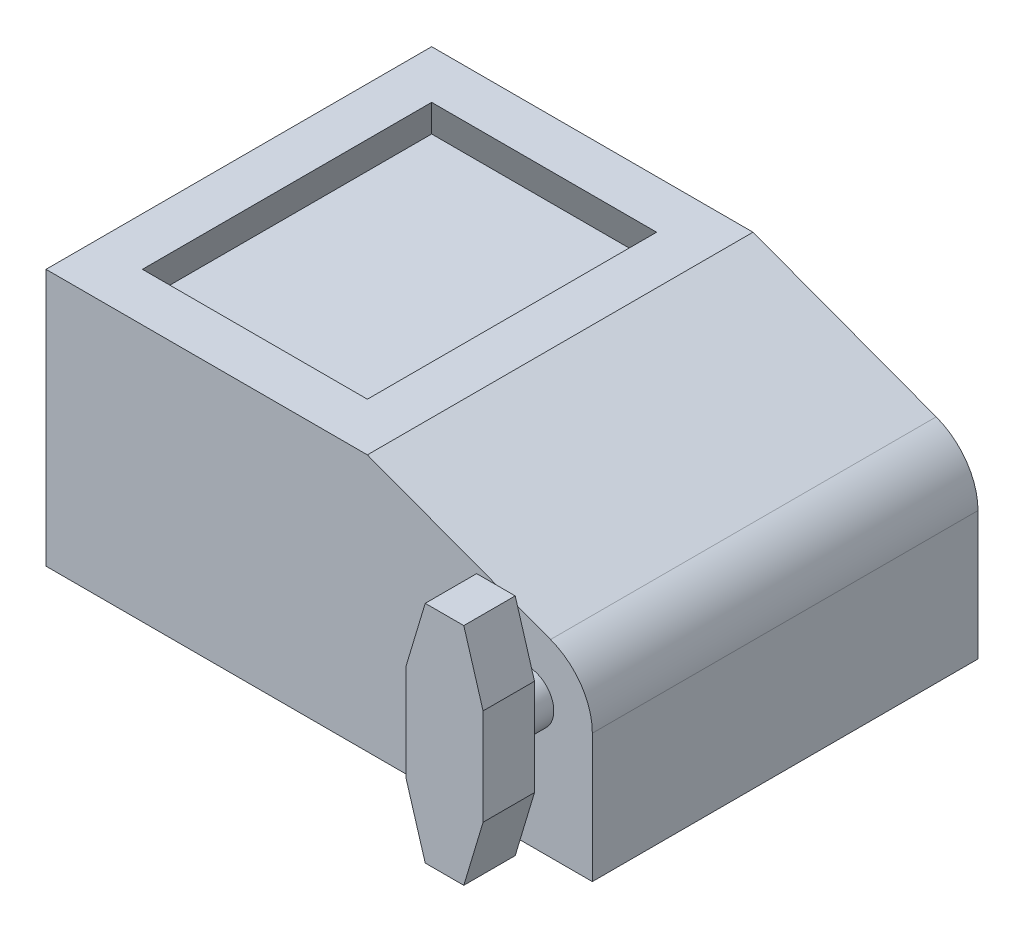
SolidWorks part; units mm, degrees
ref_plane "Front Plane" through (0, 0, 0) normal (0, 0, 1) x (1, 0, 0)
ref_plane "Top Plane" through (0, 0, 0) normal (0, 1, 0) x (1, 0, 0)
ref_plane "Right Plane" through (0, 0, 0) normal (1, 0, 0) x (0, 0, -1)
sketch "Sketch1" plane through (0, 0, 0) normal (0, 1, 0) x (1, 0, 0)
  line L1 (-25, -30) -> (25, -30)
  line L2 (-25, -30) -> (-25, 30)
  line L3 (-25, 30) -> (25, 30)
  line L4 (25, -30) -> (25, 30)
  line L5 (-25, -30) -> (25, 30) construction
  line L6 (-25, 30) -> (25, -30) construction
  point P0 (0, 0)
  dimension "D1" = 50
  dimension "D2" = 60
extrude "Boss-Extrude1" add sketch "Sketch1" along normal blind 40
sketch "Sketch2" plane through (0, 0, 30) normal (0, 0, 1) x (1, 0, 0)
  line L0 (-25, 40) -> (25, 40) construction
  line L1 (25, 40) -> (25, 0) construction
  line L2 (25, 40) -> (53.4954, 29.3692)
  line L3 (25, 0) -> (60, 0)
  line L4 (25, 40) -> (25, 0)
  line L5 (60, 20) -> (60, 0)
  circle A0 centre (50, 20) radius 10
  dimension "D3" = 20
  dimension "D1" = 20
  dimension "D2" = 25
extrude "Boss-Extrude2" add sketch "Sketch2" against normal up to surface (60 mm away)
sketch "Sketch3" plane through (0, 40, 0) normal (0, 1, 0) x (1, 0, 0)
  line L1 (-17.5, -22.5) -> (17.5, -22.5)
  line L2 (-17.5, -22.5) -> (-17.5, 22.5)
  line L3 (-17.5, 22.5) -> (17.5, 22.5)
  line L4 (17.5, -22.5) -> (17.5, 22.5)
  line L5 (-17.5, -22.5) -> (17.5, 22.5) construction
  line L6 (-17.5, 22.5) -> (17.5, -22.5) construction
  point P0 (0, 0)
  dimension "D1" = 35
  dimension "D2" = 45
extrude "Cut-Extrude1" cut sketch "Sketch3" against normal blind 8 draft 25 contours L3 L4 L1 L2 draft outward yes
sketch "Sketch4" plane through (0, 0, 30) normal (0, 0, 1) x (1, 0, 0)
  circle A0 centre (50, 20) radius 4
  dimension "D1" = 8
extrude "Boss-Extrude3" add sketch "Sketch4" along normal blind 5
sketch "Sketch5" plane through (0, 0, 35) normal (0, 0, 1) x (1, 0, 0)
  line L1 (44, 2.5) -> (56, 2.5)
  line L2 (44, 2.5) -> (44, 37.5)
  line L3 (44, 37.5) -> (56, 37.5)
  line L4 (56, 2.5) -> (56, 37.5)
  line L5 (44, 2.5) -> (56, 37.5) construction
  line L6 (44, 37.5) -> (56, 2.5) construction
  point P0 (50, 20)
  dimension "D1" = 12
  dimension "D2" = 35
extrude "Boss-Extrude4" add sketch "Sketch5" along normal blind 8
chamfer "Chamfer1" distance 3 distance2 10 2 edges at (56, 2.5, 39) (44, 37.5, 39)
chamfer "Chamfer2" distance 10 distance2 3 2 edges at (44, 2.5, 39) (56, 37.5, 39)
